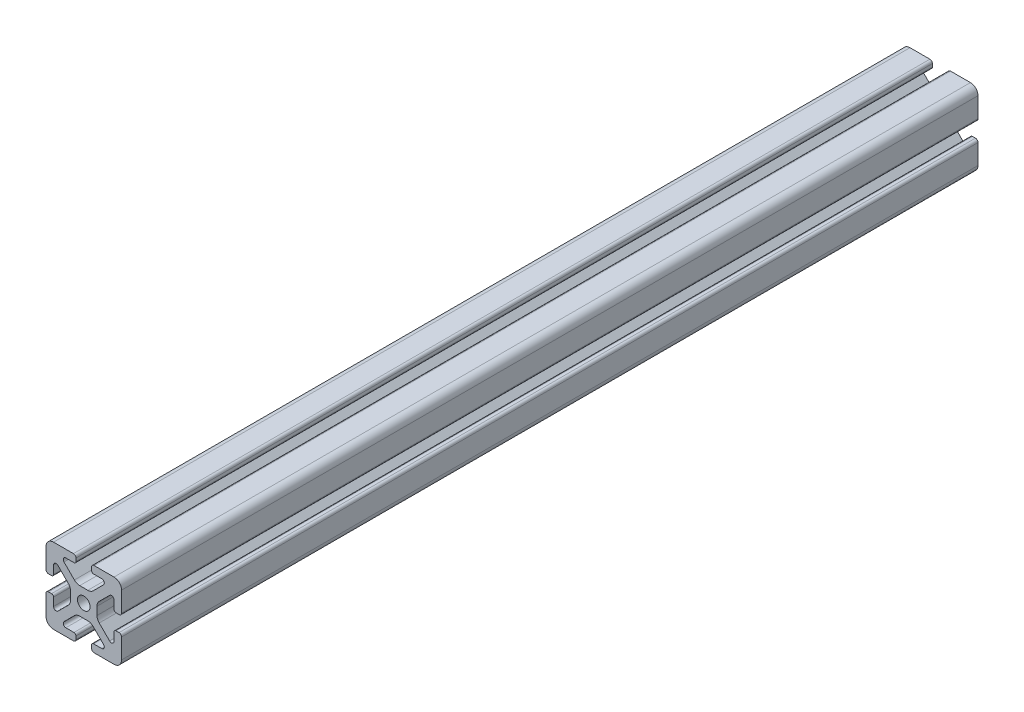
SolidWorks part; units mm, degrees
material "Alliage 1060"
ref_plane "Plan de face" through (0, 0, 0) normal (0, 0, 1) x (1, 0, 0)
ref_plane "Plan de dessus" through (0, 0, 0) normal (0, 1, 0) x (1, 0, 0)
ref_plane "Plan de droite" through (0, 0, 0) normal (1, 0, 0) x (0, 0, -1)
sketch "Esquisse1" plane through (0, 0, 0) normal (0, 0, 1) x (1, 0, 0)
  line L108 (-5.25, 1.6032) -> (-5.25, -1.6032)
  line L109 (-6.1287, -3.7245) -> (-10.2547, -7.8506)
  line L110 (-12, -7.1276) -> (-12, -3.9)
  line L111 (-12.8, -3.1) -> (-14, -3.1)
  line L112 (-15, -4.1) -> (-15, -12)
  line L113 (-12, -15) -> (-4.1, -15)
  line L114 (-3.1, -14) -> (-3.1, -12.8)
  line L115 (-3.9, -12) -> (-7.1276, -12)
  line L116 (-7.8506, -10.2547) -> (-3.7245, -6.1287)
  line L117 (-1.6032, -5.25) -> (1.6032, -5.25)
  line L118 (3.7245, -6.1287) -> (7.8506, -10.2547)
  line L119 (7.1276, -12) -> (3.9, -12)
  line L120 (3.1, -12.8) -> (3.1, -14)
  line L121 (4.1, -15) -> (12, -15)
  line L122 (15, -12) -> (15, -4.1)
  line L123 (14, -3.1) -> (12.8, -3.1)
  line L124 (12, -3.9) -> (12, -7.1276)
  line L125 (10.2547, -7.8506) -> (6.1287, -3.7245)
  line L126 (5.25, -1.6032) -> (5.25, 1.6032)
  line L127 (6.1287, 3.7245) -> (10.2547, 7.8506)
  line L128 (12, 7.1276) -> (12, 3.9)
  line L129 (12.8, 3.1) -> (14, 3.1)
  line L130 (15, 4.1) -> (15, 12)
  line L131 (12, 15) -> (4.1, 15)
  line L132 (3.1, 14) -> (3.1, 12.8)
  line L133 (3.9, 12) -> (7.1276, 12)
  line L134 (7.8506, 10.2547) -> (3.7245, 6.1287)
  line L135 (1.6032, 5.25) -> (-1.6032, 5.25)
  line L136 (-3.7245, 6.1287) -> (-7.8506, 10.2547)
  line L137 (-7.1276, 12) -> (-3.9, 12)
  line L138 (-3.1, 12.8) -> (-3.1, 14)
  line L139 (-4.1, 15) -> (-12, 15)
  line L140 (-15, 12) -> (-15, 4.1)
  line L141 (-14, 3.1) -> (-12.8, 3.1)
  line L142 (-12, 3.9) -> (-12, 7.1276)
  line L143 (-10.2547, 7.8506) -> (-6.1287, 3.7245)
  arc A42 (-2.5, 0) -> (2.5, 0) centre (0, 0) ccw
  arc A43 (2.5, 0) -> (-2.5, 0) centre (0, 0) ccw
  arc A108 (-5.25, 1.6032) -> (-6.1287, 3.7245) centre (-8.25, 1.6032) ccw
  arc A109 (-6.1287, -3.7245) -> (-5.25, -1.6032) centre (-8.25, -1.6032) ccw
  arc A110 (-12, -7.1276) -> (-10.2547, -7.8506) centre (-10.9776, -7.1276) ccw
  arc A111 (-12, -3.9) -> (-12.8, -3.1) centre (-12.8, -3.9) ccw
  arc A112 (-14, -3.1) -> (-15, -4.1) centre (-14, -4.1) ccw
  arc A113 (-15, -12) -> (-12, -15) centre (-12, -12) ccw
  arc A114 (-4.1, -15) -> (-3.1, -14) centre (-4.1, -14) ccw
  arc A115 (-3.1, -12.8) -> (-3.9, -12) centre (-3.9, -12.8) ccw
  arc A116 (-7.8506, -10.2547) -> (-7.1276, -12) centre (-7.1276, -10.9776) ccw
  arc A117 (-1.6032, -5.25) -> (-3.7245, -6.1287) centre (-1.6032, -8.25) ccw
  arc A118 (3.7245, -6.1287) -> (1.6032, -5.25) centre (1.6032, -8.25) ccw
  arc A119 (7.1276, -12) -> (7.8506, -10.2547) centre (7.1276, -10.9776) ccw
  arc A120 (3.9, -12) -> (3.1, -12.8) centre (3.9, -12.8) ccw
  arc A121 (3.1, -14) -> (4.1, -15) centre (4.1, -14) ccw
  arc A122 (12, -15) -> (15, -12) centre (12, -12) ccw
  arc A123 (15, -4.1) -> (14, -3.1) centre (14, -4.1) ccw
  arc A124 (12.8, -3.1) -> (12, -3.9) centre (12.8, -3.9) ccw
  arc A125 (10.2547, -7.8506) -> (12, -7.1276) centre (10.9776, -7.1276) ccw
  arc A126 (5.25, -1.6032) -> (6.1287, -3.7245) centre (8.25, -1.6032) ccw
  arc A127 (6.1287, 3.7245) -> (5.25, 1.6032) centre (8.25, 1.6032) ccw
  arc A128 (12, 7.1276) -> (10.2547, 7.8506) centre (10.9776, 7.1276) ccw
  arc A129 (12, 3.9) -> (12.8, 3.1) centre (12.8, 3.9) ccw
  arc A130 (14, 3.1) -> (15, 4.1) centre (14, 4.1) ccw
  arc A131 (15, 12) -> (12, 15) centre (12, 12) ccw
  arc A132 (4.1, 15) -> (3.1, 14) centre (4.1, 14) ccw
  arc A133 (3.1, 12.8) -> (3.9, 12) centre (3.9, 12.8) ccw
  arc A134 (7.8506, 10.2547) -> (7.1276, 12) centre (7.1276, 10.9776) ccw
  arc A135 (1.6032, 5.25) -> (3.7245, 6.1287) centre (1.6032, 8.25) ccw
  arc A136 (-3.7245, 6.1287) -> (-1.6032, 5.25) centre (-1.6032, 8.25) ccw
  arc A137 (-7.1276, 12) -> (-7.8506, 10.2547) centre (-7.1276, 10.9776) ccw
  arc A138 (-3.9, 12) -> (-3.1, 12.8) centre (-3.9, 12.8) ccw
  arc A139 (-3.1, 14) -> (-4.1, 15) centre (-4.1, 14) ccw
  arc A140 (-12, 15) -> (-15, 12) centre (-12, 12) ccw
  arc A141 (-15, 4.1) -> (-14, 3.1) centre (-14, 4.1) ccw
  arc A142 (-12.8, 3.1) -> (-12, 3.9) centre (-12.8, 3.9) ccw
  arc A143 (-10.2547, 7.8506) -> (-12, 7.1276) centre (-10.9776, 7.1276) ccw
extrude "Boss.-Extru.1" add sketch "Esquisse1" along normal blind 340
